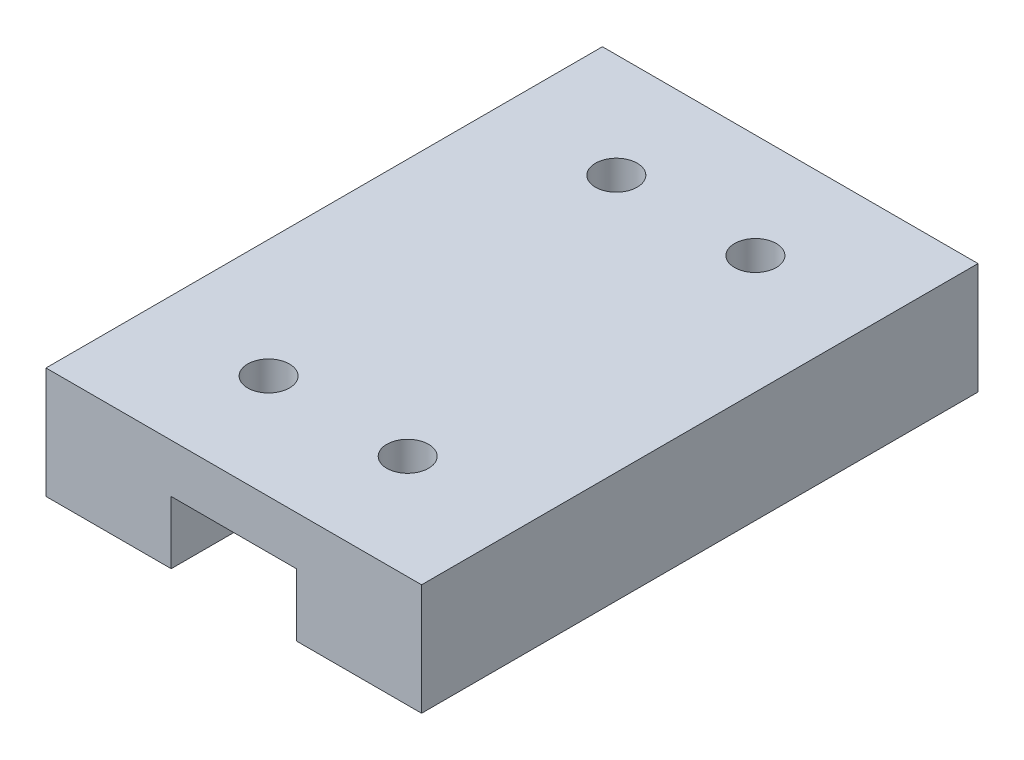
SolidWorks part; units mm, degrees
material "AISI 304"
ref_plane "前视基准面" through (0, 0, 0) normal (0, 0, 1) x (1, 0, 0)
ref_plane "上视基准面" through (0, 0, 0) normal (0, 1, 0) x (1, 0, 0)
ref_plane "右视基准面" through (0, 0, 0) normal (1, 0, 0) x (0, 0, -1)
sketch "草图1" plane through (0, 0, 0) normal (0, 0, 1) x (1, 0, 0)
  line L0 (0, 11.4966) -> (0, 0) construction
  line L1 (-4.5, 4.5) -> (4.5, 4.5)
  line L2 (4.5, 4.5) -> (4.5, 0)
  line L3 (4.5, 0) -> (13.5, 0)
  line L4 (13.5, 0) -> (13.5, 8)
  line L5 (13.5, 8) -> (-13.5, 8)
  line L6 (-13.5, 0) -> (-13.5, 8)
  line L7 (-4.5, 0) -> (-13.5, 0)
  line L8 (-4.5, 4.5) -> (-4.5, 0)
  dimension "D1" = 3.5
  dimension "D2" = 27
  dimension "D3" = 9
  dimension "D4" = 8
extrude "凸台-拉伸1" add sketch "草图1" along normal mid plane 40
sketch "草图2" plane through (0, 8, 0) normal (0, 1, 0) x (1, 0, 0)
  line L0 (0, 15.7064) -> (0, 0) construction
  line L1 (0, 0) -> (15.5398, 0) construction
  circle A0 centre (5, 12.5) radius 1.5
  circle A1 centre (-5, 12.5) radius 1.5
  circle A2 centre (-5, -12.5) radius 1.5
  circle A3 centre (5, -12.5) radius 1.5
  dimension "D1" = 3
  dimension "D2" = 25
  dimension "D3" = 10
extrude "切除-拉伸1" cut sketch "草图2" against normal blind 2.5
sketch "草图3" plane through (-13.5, 0, 0) normal (-1, 0, 0) x (0, 0, 1)
  line L0 (10, 8) -> (4.8454, 16.5691)
  line L1 (20, 8) -> (-20, 8) construction
  line L2 (4.8454, 16.5691) -> (-9.4, 8)
  line L3 (10, 8) -> (-9.4, 8)
  line L4 (295.6762, 489.8644) -> (-402.7065, 69.7613) construction
  line L5 (20, 8) -> (20, 0) construction
  dimension "D1" = 10
  dimension "D2" = 10
